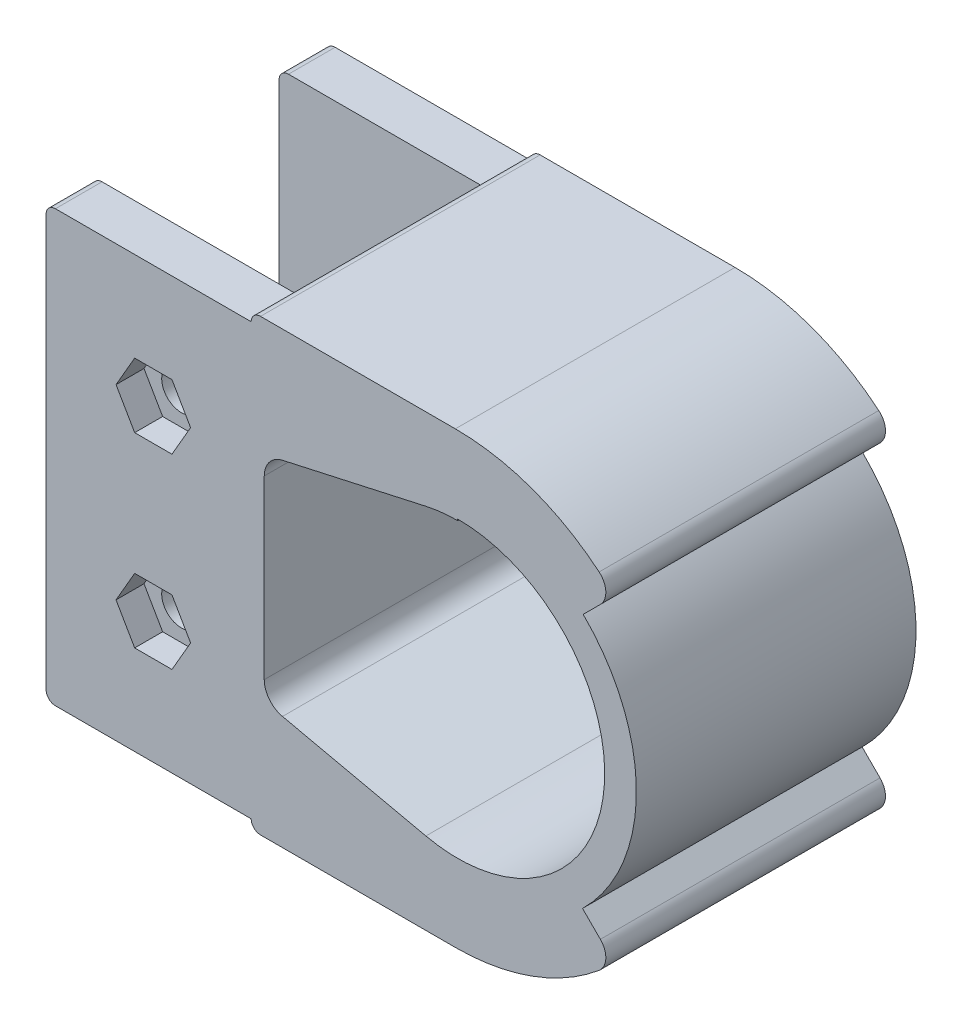
SolidWorks part; units mm, degrees
ref_plane "前视基准面" through (0, 0, 0) normal (0, 0, 1) x (1, 0, 0)
ref_plane "上视基准面" through (0, 0, 0) normal (0, 1, 0) x (1, 0, 0)
ref_plane "右视基准面" through (0, 0, 0) normal (1, 0, 0) x (0, 0, -1)
sketch "草图1" plane through (0, 0, 0) normal (0, 0, 1) x (1, 0, 0)
  line L0 (-18.3287, -10.9251) -> (-2.946, -14.3416)
  line L1 (-2.946, 14.4859) -> (-18.3287, 11.0694)
  line L2 (-19.5035, 9.605) -> (-19.5035, -9.4608)
  line L3 (-18.5455, -11.9013) -> (-3.1628, -15.3179)
  line L4 (-3.1628, 15.4621) -> (-18.5455, 12.0456)
  line L5 (-20.5035, 9.605) -> (-20.5035, -9.4608)
  line L6 (-19.2827, -15.2204) -> (-3.9, -18.637)
  line L7 (-3.9, 18.7812) -> (-19.2827, 15.3647)
  line L8 (-23.9035, 9.605) -> (-23.9035, -9.4608)
  arc A0 (-19.5035, -9.4608) -> (-18.3287, -10.9251) centre (-18.0035, -9.4608) ccw
  arc A1 (-2.946, -14.3416) -> (-2.946, 14.4859) centre (0.2553, 0.0721) ccw
  arc A2 (-18.3287, 11.0694) -> (-19.5035, 9.605) centre (-18.0035, 9.605) ccw
  arc A3 (-3.1628, -15.3179) -> (-3.1628, 15.4621) centre (0.2553, 0.0721) ccw
  arc A4 (-18.5455, 12.0456) -> (-20.5035, 9.605) centre (-18.0035, 9.605) ccw
  arc A5 (-20.5035, -9.4608) -> (-18.5455, -11.9013) centre (-18.0035, -9.4608) ccw
  arc A6 (-3.9, -18.637) -> (-3.9, 18.7812) centre (0.2553, 0.0721) ccw
  arc A7 (-19.2827, 15.3647) -> (-23.9035, 9.605) centre (-18.0035, 9.605) ccw
  arc A8 (-23.9035, -9.4608) -> (-19.2827, -15.2204) centre (-18.0035, -9.4608) ccw
  dimension "D1" = 1
  dimension "D2" = 4.4
extrude "凸台-拉伸1" add sketch "草图1" along normal blind 30 contours L8 A8 L6 A6 L7 A7 A5 L5 A4 L4 A3 L3
sketch "草图2" plane through (0, 0, 30) normal (0, 0, 1) x (1, 0, 0)
  line L0 (0.2553, -19.0929) -> (-21.9035, -19.0929)
  line L1 (-23.9035, -17.0929) -> (-23.9035, -9.4608)
  line L2 (-23.9035, 9.605) -> (-23.9035, -9.4608) construction
  line L4 (-18.5455, -11.9013) -> (-3.1628, -15.3179) construction
  line L6 (-18.5455, -11.9013) -> (-3.1628, -15.3179)
  line L7 (0.2553, -19.0929) -> (0.2553, -15.6929)
  line L8 (-23.9035, -9.4608) -> (-20.5035, -9.4608)
  arc A0 (-3.9, -18.637) -> (-3.9, 18.7812) centre (0.2553, 0.0721) ccw construction
  arc A1 (-3.1628, -15.3179) -> (-3.1628, 15.4621) centre (0.2553, 0.0721) ccw construction
  arc A2 (-20.5035, -9.4608) -> (-18.5455, -11.9013) centre (-18.0035, -9.4608) ccw construction
  arc A3 (-3.1628, -15.3179) -> (0.2553, -15.6929) centre (0.2553, 0.0721) ccw
  arc A4 (-20.5035, -9.4608) -> (-18.5455, -11.9013) centre (-18.0035, -9.4608) ccw
  arc A5 (-21.9035, -19.0929) -> (-23.9035, -17.0929) centre (-21.9035, -17.0929) cw
  dimension "D1" = 2
extrude "凸台-拉伸2" add sketch "草图2" against normal up to surface (30 mm away) up to face at (-11.0164, 0.0721, 0)
sketch "草图3" plane through (0, 0, 0) normal (0, 0, -1) x (-1, 0, 0)
  line L0 (21.9035, -19.0929) -> (21.9035, -23.0929)
  line L1 (20.9035, -24.0929) -> (0, -24.0929)
  line L5 (-15.5579, -15.5579) -> (-13.6423, -13.6423)
  line L6 (0, 0) -> (0, -13.0037) construction
  line L10 (-0.2553, -19.0929) -> (21.9035, -19.0929)
  line L11 (23.9035, -17.0929) -> (23.9035, 9.605)
  line L12 (19.2827, 15.3647) -> (3.9, 18.7812)
  line L13 (-0.2553, -19.0929) -> (21.9035, -19.0929)
  arc A0 (21.9035, -23.0929) -> (20.9035, -24.0929) centre (20.9035, -23.0929) cw
  arc A2 (0, -24.0929) -> (-15.4241, -18.5085) centre (0, 0) cw
  arc A3 (3.9, 18.7812) -> (-0.2553, -19.0929) centre (-0.2553, 0.0721) ccw construction
  arc A5 (-15.5579, -15.5579) -> (-15.4241, -18.5085) centre (-14.1437, -16.9721) ccw
  arc A8 (3.9, 18.7812) -> (-0.2553, -19.0929) centre (-0.2553, 0.0721) ccw
  arc A9 (21.9035, -19.0929) -> (23.9035, -17.0929) centre (21.9035, -17.0929) ccw
  arc A10 (23.9035, 9.605) -> (19.2827, 15.3647) centre (18.0035, 9.605) ccw
  arc A11 (-13.6423, -13.6423) -> (-0.2553, -19.0929) centre (-0.2553, 0.0721) ccw
  point P12 (0, -24.0929)
  dimension "D2" = 1
  dimension "D3" = 45
  dimension "D4" = 2
  dimension "D1" = 0
extrude "凸台-拉伸3" add sketch "草图3" against normal up to surface (30 mm away) up to face at (-11.0164, 0.0721, 30)
mirror "镜向1" about plane through (0, 0, 0) normal (0, 1, 0) of "凸台-拉伸2", "凸台-拉伸3"
sketch "草图9" plane through (-23.9035, 0, 0) normal (-1, 0, 0) x (0, 0, 1)
  line L0 (30, 23.0929) -> (0, 23.0929) construction
  line L1 (0, -23.0929) -> (5, -23.0929)
  line L2 (0, -23.0929) -> (0, 23.0929)
  line L3 (0, 23.0929) -> (5, 23.0929)
  line L4 (5, -23.0929) -> (5, 23.0929)
  line L5 (30, -23.0929) -> (0, -23.0929) construction
  line L6 (25, -23.0929) -> (30, -23.0929)
  line L7 (25, -23.0929) -> (25, 23.0929)
  line L8 (25, 23.0929) -> (30, 23.0929)
  line L9 (30, -23.0929) -> (30, 23.0929)
  line L10 (15, 23.0929) -> (15, -23.0929) construction
  line M9 (0, 17.0929) -> (0, -17.0929)
  line M10 (0, -17.0929) -> (30, -17.0929)
  line M11 (30, -17.0929) -> (30, 17.0929)
  line M12 (30, 17.0929) -> (0, 17.0929)
  dimension "D1" = 20
extrude "凸台-拉伸6" add sketch "草图9" along normal blind 20 and the other way up to next contours L7 M10 M11 M12 | L9 L8 L7 M12 | L6 L9 L7 M10 | L4 L3 L2 M12 | L4 M10 M12 M9 | L1 L4 L2 M10
fillet "圆角3" radius 1 4 edges at (-43.9035, 23.0929, 27.5) (-43.9035, -23.0929, 27.5) (-43.9035, -23.0929, 2.5) (-43.9035, 23.0929, 2.5)
sketch "草图10" plane through (0, 0, 30) normal (0, 0, 1) x (1, 0, 0)
  line L0 (-32.4035, 23.0929) -> (-32.4035, -23.0929) construction
  line L1 (-42.9035, 23.0929) -> (-21.9035, 23.0929) construction
  line L2 (-42.9035, -23.0929) -> (-21.9035, -23.0929) construction
  line L3 (-43.9035, 0) -> (-20.5035, 0) construction
  line L4 (-43.9035, -22.0929) -> (-43.9035, 22.0929) construction
  line L5 (-20.5035, 9.4608) -> (-20.5035, -9.4608) construction
  line L7 (-32.4035, 6) -> (-28.9394, 8)
  line L8 (-28.9394, 8) -> (-28.9394, 12)
  line L9 (-28.9394, 12) -> (-32.4035, 14)
  line L10 (-32.4035, 14) -> (-35.8676, 12)
  line L11 (-35.8676, 12) -> (-35.8676, 8)
  line L12 (-35.8676, 8) -> (-32.4035, 6)
  line L13 (-35.8676, -12) -> (-32.4035, -14)
  line L14 (-32.4035, -14) -> (-28.9394, -12)
  line L15 (-28.9394, -12) -> (-28.9394, -8)
  line L16 (-28.9394, -8) -> (-32.4035, -6)
  line L17 (-32.4035, -6) -> (-35.8676, -8)
  line L18 (-35.8676, -8) -> (-35.8676, -12)
  circle A0 centre (-32.4035, -10) radius 2.1
  circle A1 centre (-32.4035, 10) radius 2.1
  circle A2 centre (-32.4035, 10) radius 3.4641 construction
  circle A3 centre (-32.4035, -10) radius 3.4641 construction
  dimension "D1" = 20
  dimension "D2" = 4.2
  dimension "D3" = 4
extrude "切除-拉伸4" cut sketch "草图10" against normal through all both and the other way through all contours A1 | A0
sketch "草图11" plane through (0, 0, 30) normal (0, 0, 1) x (1, 0, 0)
  line L1 (-28.4035, -10) -> (-30.4035, -6.5359)
  line L2 (-30.4035, -6.5359) -> (-34.4035, -6.5359)
  line L3 (-34.4035, -6.5359) -> (-36.4035, -10)
  line L4 (-36.4035, -10) -> (-34.4035, -13.4641)
  line L5 (-34.4035, -13.4641) -> (-30.4035, -13.4641)
  line L6 (-30.4035, -13.4641) -> (-28.4035, -10)
  line L7 (-28.4035, 10) -> (-30.4035, 13.4641)
  line L8 (-30.4035, 13.4641) -> (-34.4035, 13.4641)
  line L9 (-34.4035, 13.4641) -> (-36.4035, 10)
  line L10 (-36.4035, 10) -> (-34.4035, 6.5359)
  line L11 (-34.4035, 6.5359) -> (-30.4035, 6.5359)
  line L12 (-30.4035, 6.5359) -> (-28.4035, 10)
  circle A0 centre (-32.4035, -10) radius 3.4641 construction
  circle A1 centre (-32.4035, 10) radius 3.4641 construction
  dimension "D1" = 4
extrude "切除-拉伸5" cut sketch "草图11" against normal blind 3
ref_plane "基准面1" through (0, 0, 15) normal (0, 0, 1) x (1, 0, 0)
mirror "镜向3" about plane through (0, 0, 15) normal (0, 0, 1) of "切除-拉伸5"
